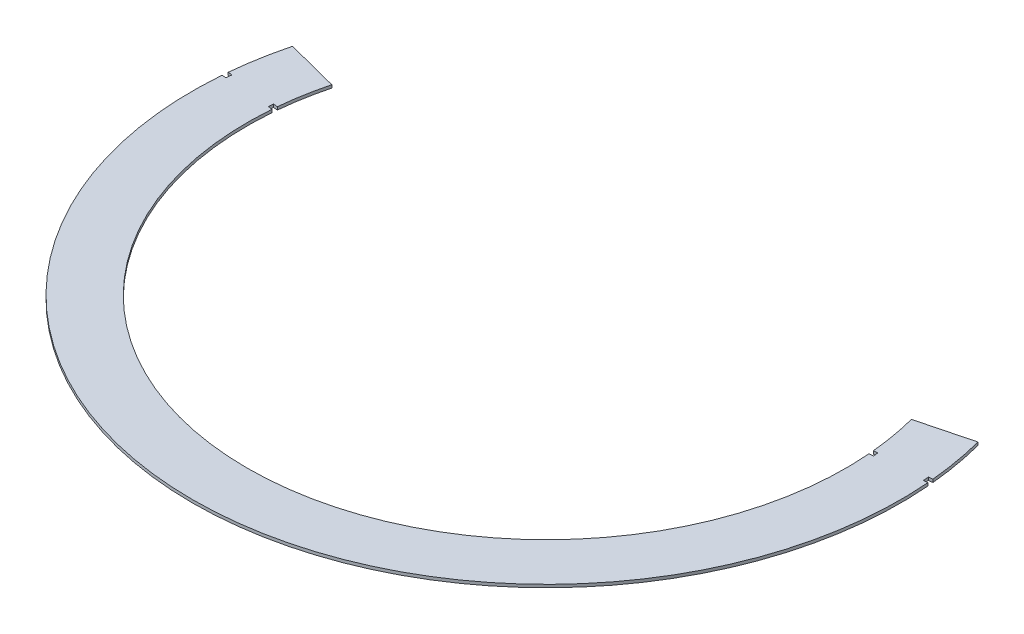
SolidWorks part; units mm, degrees
material "6061 Alloy"
ref_plane "Front" through (0, 0, 0) normal (0, 0, 1) x (1, 0, 0)
ref_plane "Top" through (0, 0, 0) normal (0, 1, 0) x (1, 0, 0)
ref_plane "Right" through (0, 0, 0) normal (1, 0, 0) x (0, 0, -1)
sketch "Sketch1" plane through (0, 0, 0) normal (0, 1, 0) x (1, 0, 0)
  line L0 (0, 0) -> (0, -71.22) construction
  line L1 (70.9921, 5.6932) -> (83.9505, 6.7324)
  line L2 (-70.9921, 5.6932) -> (-83.9505, 6.7324)
  arc A0 (-70.9921, 5.6932) -> (70.9921, 5.6932) centre (0, 0) ccw
  arc A1 (-83.9505, 6.7324) -> (83.9505, 6.7324) centre (0, 0) ccw
  dimension "D1" = 142.44
  dimension "D2" = 168.44
  dimension "D3" = 189.17
extrude "Boss-Extrude1" add sketch "Sketch1" along normal mid plane 0.7
sketch "Sketch2" plane through (0, 0.35, 0) normal (0, 1, 0) x (1, 0, 0)
  line L0 (-68.9515, 17.8321) -> (0, 0) construction
  line L1 (0, 0) -> (68.9515, 17.8321) construction
  line L2 (0, 0) -> (0, -71.22) construction
  line L3 (83.9505, 6.7324) -> (70.9921, 5.6932) construction
  line L4 (-70.9921, 5.6932) -> (-83.9505, 6.7324) construction
  line L5 (82.9643, 6.6533) -> (71.9797, 5.7724)
  line L6 (-71.9797, 5.7724) -> (-82.9643, 6.6533)
  line L7 (-68.9515, 17.8321) -> (-81.5374, 21.087)
  line L8 (68.9515, 17.8321) -> (81.5374, 21.087)
  line L9 (0, 0) -> (-70.8921, 6.8261) construction
  line L10 (-70.8921, 6.8261) -> (-71.8875, 6.922)
  line L11 (-71.8875, 6.922) -> (-71.9797, 5.7724)
  line L12 (-83.8323, 8.0721) -> (-82.8369, 7.9763)
  line L13 (-82.8369, 7.9763) -> (-82.9643, 6.6533)
  line L14 (82.8369, 7.9763) -> (82.9643, 6.6533)
  line L15 (83.8323, 8.0721) -> (82.8369, 7.9763)
  line L16 (71.8875, 6.922) -> (71.9797, 5.7724)
  line L17 (70.8921, 6.8261) -> (71.8875, 6.922)
  line L18 (71.9797, 5.7724) -> (82.9643, 6.6533)
  arc A0 (70.8921, 6.8261) -> (68.9515, 17.8321) centre (0, 0) ccw
  arc A1 (83.8323, 8.0721) -> (81.5374, 21.087) centre (0, 0) ccw
  arc A2 (-81.5374, 21.087) -> (-83.8323, 8.0721) centre (0, 0) ccw
  arc A3 (-68.9515, 17.8321) -> (-70.8921, 6.8261) centre (0, 0) ccw
  line M9 (-70.9921, 5.6932) -> (-83.9505, 6.7324)
  line M11 (83.9505, 6.7324) -> (70.9921, 5.6932)
  dimension "D1" = 151
  dimension "D2" = 9
  dimension "D3" = 1
extrude "Boss-Extrude2" add sketch "Sketch2" against normal up to surface (0.7 mm away) contours L15 A1 L8 A0 L17 L16 L14 M11 | A3 L7 A2 L12 L13 L11 L10 M9 up to face at (0, -0.35, 35.7536)
